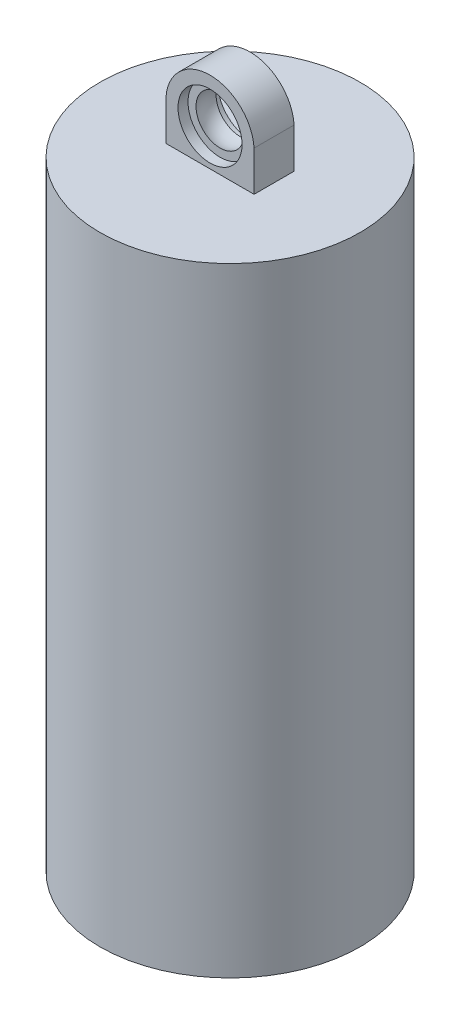
SolidWorks part; units mm, degrees
ref_plane "前视基准面" through (0, 0, 0) normal (0, 0, 1) x (1, 0, 0)
ref_plane "上视基准面" through (0, 0, 0) normal (0, 1, 0) x (1, 0, 0)
ref_plane "右视基准面" through (0, 0, 0) normal (1, 0, 0) x (0, 0, -1)
sketch "草图1" plane through (0, 0, 0) normal (0, 1, 0) x (1, 0, 0)
  circle A0 centre (0, 0) radius 32.5
  dimension "D1" = 65
extrude "凸台-拉伸1" add sketch "草图1" along normal blind 154.5
sketch "草图2" plane through (0, 0, 0) normal (0, -1, 0) x (1, 0, 0)
  circle A0 centre (0, 0) radius 12.5
  dimension "D1" = 25
extrude "凸台-拉伸2" add sketch "草图2" along normal blind 6
sketch "草图3" plane through (0, -6, 0) normal (0, -1, 0) x (1, 0, 0)
  circle A0 centre (0, 0) radius 6
  dimension "D1" = 12
extrude "切除-拉伸1" cut sketch "草图3" against normal blind 80
sketch "草图4" plane through (0, 0, 0) normal (0, 0, 1) x (1, 0, 0)
  line L0 (32.5, 154.5) -> (-32.5, 154.5) construction
  line L1 (-11, 154.5) -> (11, 154.5)
  line L2 (-11, 154.5) -> (-11, 164.5)
  line L4 (11, 154.5) -> (11, 164.5)
  line L5 (0, 193.283) -> (0, 138.3299) construction
  arc A0 (-11, 164.5) -> (11, 164.5) centre (0, 163.7613) cw
  circle A1 centre (0, 163.7613) radius 8
  dimension "D4" = 16
  dimension "D1" = 22
  dimension "D2" = 11
  dimension "D3" = 10
extrude "凸台-拉伸3" add sketch "草图4" against normal mid plane 10
sketch "草图5" plane through (0, 0, 0) normal (0, 0, 1) x (1, 0, 0)
  circle A0 centre (0, 163.7613) radius 8
extrude "凸台-拉伸4" add sketch "草图5" along normal mid plane 5
ref_plane "基准面4" through (0, 0, 4.5) normal (0, 0, 1) x (1, 0, 0)
sketch "草图7" plane through (0, 0, 2.5) normal (0, 0, 1) x (1, 0, 0)
  circle A0 centre (0, 163.7613) radius 6
  dimension "D1" = 12
sketch "草图8" plane through (0, 0, 4.5) normal (0, 0, 1) x (1, 0, 0)
  circle A0 centre (0, 163.7613) radius 4
  dimension "D1" = 8
loft "放样1" add profiles "草图8", "草图7"
mirror "镜向1" about plane through (0, 0, 0) normal (0, 0, 1) of "放样1"
sketch "草图9" plane through (0, 0, 4.5) normal (0, 0, 1) x (1, 0, 0)
  circle A0 centre (0, 166.7613) radius 2.5
  dimension "D1" = 5
extrude "切除-拉伸2" cut sketch "草图9" against normal blind 31
sketch "草图10" plane through (0, 0, 4.5) normal (0, 0, 1) x (1, 0, 0)
  circle A0 centre (0, 163.7613) radius 6
  circle A4 centre (0, 163.7613) radius 8 construction
  point P5 (0, 166.7613)
extrude "切除-拉伸3" cut sketch "草图10" against normal blind 17
sketch "草图11" plane through (0, 0, 0) normal (0, 0, 1) x (1, 0, 0)
  line L0 (0, 170.2613) -> (0, 157.2613)
  arc A0 (0, 157.2613) -> (0, 170.2613) centre (0, 163.7613) ccw
  dimension "D1" = 13
revolve "切除-旋转1" cut sketch "草图11" angle 360 about L0
